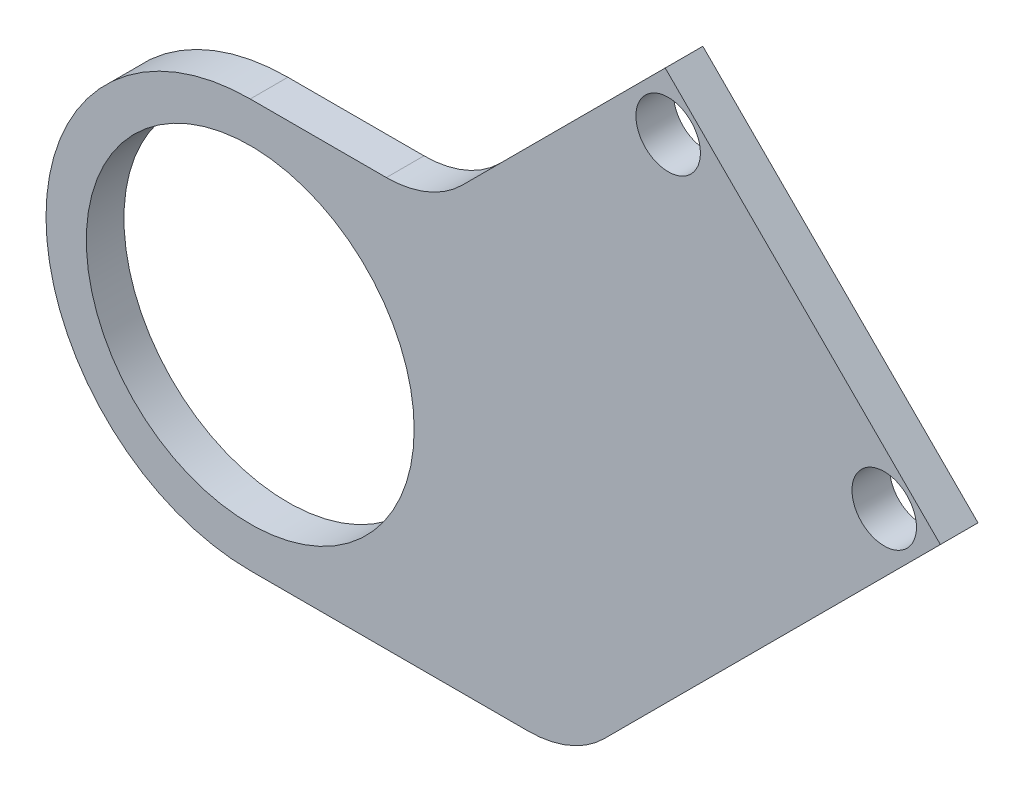
SolidWorks part; units mm, degrees
material "Foam"
ref_plane "Front Plane" through (0, 0, 0) normal (0, 0, 1) x (1, 0, 0)
ref_plane "Top Plane" through (0, 0, 0) normal (0, 1, 0) x (1, 0, 0)
ref_plane "Right Plane" through (0, 0, 0) normal (1, 0, 0) x (0, 0, -1)
sketch "Sketch1" plane through (0, 0, 0) normal (0, 0, 1) x (1, 0, 0)
  line L0 (51.4027, 28) -> (24.5327, 1.1299) construction
  line L1 (0, -19) -> (30, -19)
  line L2 (17.3202, 8.3424) -> (31.7452, -6.0825) construction
  line L3 (31.7452, -6.0825) -> (58.6152, 20.7875) construction
  line L4 (17.3202, 8.3424) -> (44.1902, 35.2125) construction
  line L5 (30, -19) -> (64.2014, 15.2014)
  line L6 (44.1902, 35.2125) -> (58.6152, 20.7875)
  line L7 (64.2014, 15.2014) -> (58.6152, 20.7875)
  line L8 (0, 0) -> (0, 28) construction
  line L9 (44.1902, 35.2125) -> (38.6041, 40.7986)
  line L10 (38.6041, 40.7986) -> (16.8055, 19)
  line L11 (16.8055, 19) -> (0, 19)
  line L12 (0, 0) -> (-19, 0) construction
  line L19 (51.4027, 28) -> (0, 28) construction
  arc A0 (0, 19) -> (0, -19) centre (0, 0) ccw
  circle A1 centre (0, 0) radius 2.5
  dimension "D1" = 38
  dimension "D5" = 30
  dimension "D6" = 5
  dimension "D14" = 45
  dimension "D2" = 20.4
  dimension "D3" = 38
  dimension "D4" = 36.2
  dimension "D13" = 28
extrude "Boss-Extrude1" add sketch "Sketch1" along normal blind 3.5
sketch "Sketch2" plane through (0, 0, 3.5) normal (0, 0, 1) x (1, 0, 0)
  line L0 (51.4027, 28) -> (31.4988, 8.0961) construction
  line L1 (64.2014, 15.2014) -> (38.6041, 40.7986) construction
  circle A0 centre (38.8781, 35.5749) radius 1.5
  circle A1 centre (58.9776, 15.4754) radius 1.5
  dimension "D1" = 3
  dimension "D2" = 3.5
  dimension "D3" = 28.425
extrude "Cut-Extrude1" cut sketch "Sketch2" against normal through all
fillet "Fillet1" radius 10 2 edges at (16.8055, 19, 1.75) (30, -19, 1.75)
sketch "Sketch3" plane through (0, 0, 3.5) normal (0, 0, 1) x (1, 0, 0)
  circle A0 centre (0, 0) radius 15.25
  circle A1 centre (38.8781, 35.5749) radius 3
  circle A2 centre (58.9776, 15.4754) radius 3
  dimension "D1" = 6
  dimension "D2" = 30.5
extrude "Cut-Extrude2" cut sketch "Sketch3" against normal through all
equation "\"D2@Sketch1\"=20.20mm+\"cut_free@Parameters@Parameters.SLDPRT\""
